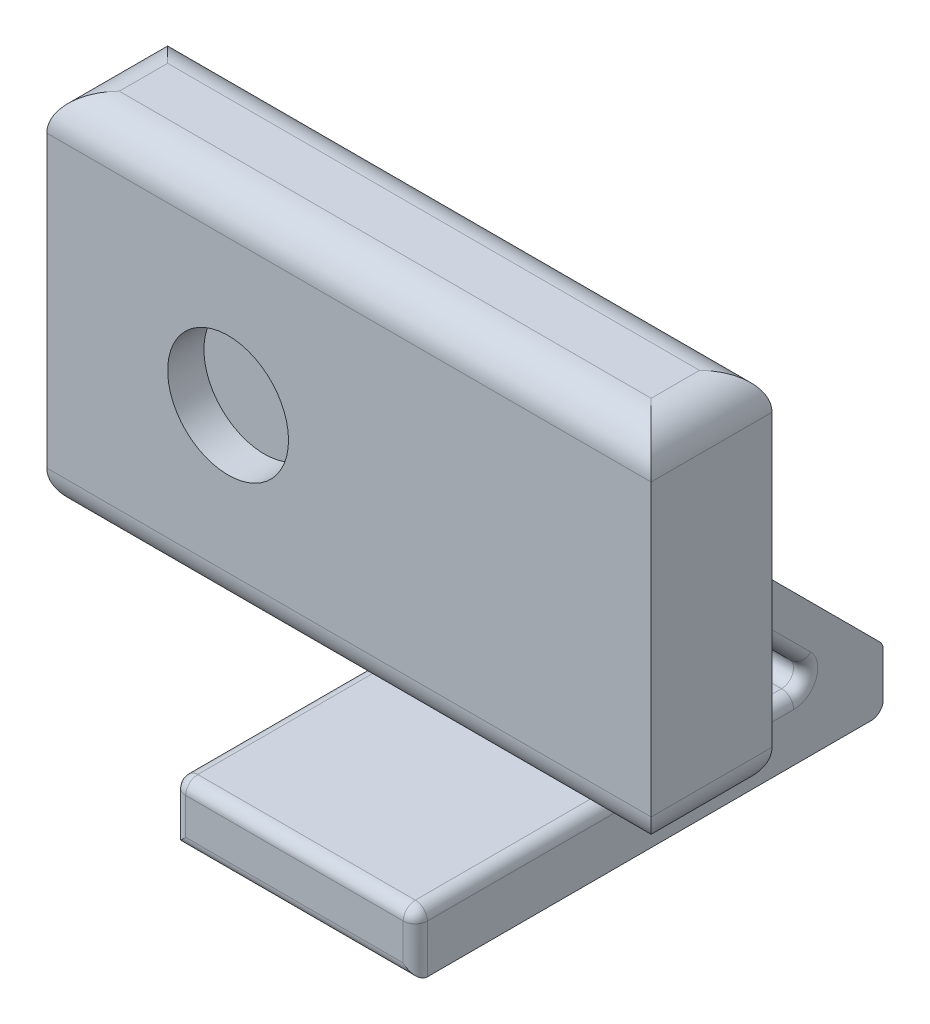
SolidWorks part; units mm, degrees
ref_plane "정면" through (0, 0, 0) normal (0, 0, 1) x (1, 0, 0)
ref_plane "윗면" through (0, 0, 0) normal (0, 1, 0) x (1, 0, 0)
ref_plane "우측면" through (0, 0, 0) normal (1, 0, 0) x (0, 0, -1)
sketch "스케치1" plane through (0, 0, 0) normal (0, 0, 1) x (1, 0, 0)
  line L5 (-25, 15) -> (25, 15)
  line L6 (-25, 15) -> (-25, -15)
  line L7 (-25, -15) -> (25, -15)
  line L8 (25, 15) -> (25, -15)
  line L9 (-25, 15) -> (25, -15) construction
  line L10 (-25, -15) -> (25, 15) construction
  point P0 (0, 0)
  dimension "D1" = 50
  dimension "D2" = 30
extrude "보스-돌출1" add sketch "스케치1" along normal blind 10
sketch "스케치2" plane through (0, 0, 0) normal (1, 0, 0) x (0, 0, -1)
  line L0 (0, 0) -> (24.2012, -24.2012)
  line L1 (24.2012, -24.2012) -> (24.2012, -29.2012)
  line L2 (24.2012, -29.2012) -> (-14.51, -29.2012)
  line L3 (-14.51, -29.2012) -> (-14.51, -24.2012)
  line L4 (-14.51, -24.2012) -> (19.2012, -24.2012)
  line L5 (0, -5) -> (19.2012, -24.2012)
  line L6 (0, -15) -> (0, 15) construction
  line L7 (0, 0) -> (0, -5)
  dimension "D1" = 5
  dimension "D2" = 5
  dimension "D3" = 5
  dimension "D4" = 5
extrude "보스-돌출2" add sketch "스케치2" along normal mid plane 20
sketch "스케치3" plane through (0, 0, 10) normal (0, 0, 1) x (1, 0, 0)
  circle A0 centre (-10, 0) radius 5
  dimension "D1" = 10
  dimension "D2" = 10
extrude "컷-돌출1" cut sketch "스케치3" against normal blind 3
fillet "필렛1" radius 3 8 edges at (-25, -15, 5) (0, -15, 10) (25, -15, 5) (0, -15, 0) (25, 15, 5) (0, 15, 10) (-25, 15, 5) (0, 15, 0)
fillet "필렛2" radius 1 11 edges at (10, -14.6006, -9.6006) (-10, -14.6006, -9.6006) (0, -24.2012, -19.2012) (10, -24.2012, -2.3456) (-10, -24.2012, -2.3456) (0, -24.2012, 14.51) (10, -26.7012, 14.51) (0, -29.2012, 14.51) (-10, -26.7012, 14.51) (0, -24.2012, -24.2012) (0, -29.2012, -24.2012)
